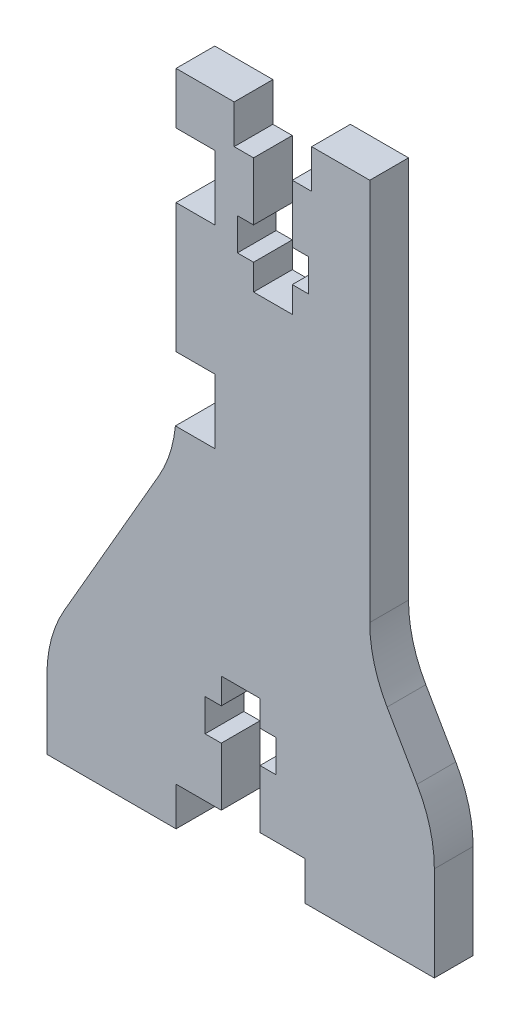
SolidWorks part; units mm, degrees
ref_plane "Alzado" through (0, 0, 0) normal (0, 0, 1) x (1, 0, 0)
ref_plane "Planta" through (0, 0, 0) normal (0, 1, 0) x (1, 0, 0)
ref_plane "Vista lateral" through (0, 0, 0) normal (1, 0, 0) x (0, 0, -1)
sketch "Croquis1" plane through (0, 0, 0) normal (0, 0, 1) x (1, 0, 0)
  line L0 (-15, -24) -> (-15, -19)
  line L1 (15, -24) -> (-15, -24)
  line L2 (15, -24) -> (15, 24) construction
  line L3 (15, 24) -> (-15, 24) construction
  line L4 (-15, -24) -> (-15, 24) construction
  line L5 (15, -24) -> (-15, 24) construction
  line L6 (15, 24) -> (-15, -24) construction
  line L7 (-15, -19) -> (-5, -1.6795)
  line L8 (-5, -1.6795) -> (-5, 24)
  line L9 (-5, 24) -> (10, 24)
  line L10 (10, 24) -> (10, -8.3397)
  line L11 (10, -8.3397) -> (15, -17)
  line L12 (15, -17) -> (15, -24)
  line L14 (-15, -24) -> (-5, -24)
  line L15 (-15, -24) -> (-15, -27)
  line L16 (-15, -27) -> (-5, -27)
  line L17 (-5, -24) -> (-5, -27)
  line L18 (15, -24) -> (5, -24)
  line L19 (15, -24) -> (15, -27)
  line L20 (15, -27) -> (5, -27)
  line L21 (5, -24) -> (5, -27)
  point P0 (0, 0)
  dimension "D1" = 48
  dimension "D2" = 30
  dimension "D3" = 10
  dimension "D4" = 5
  dimension "D5" = 5
  dimension "D6" = 7
  dimension "D7" = 3
  dimension "D8" = 10
  dimension "D9" = 10
  dimension "D10" = 30
  dimension "D11" = 30
extrude "Saliente-Extruir1" add sketch "Croquis1" along normal blind 3 contours L12 L11 L10 L9 L8 L7 L0 L1 | L17 L1 L15 L16 | L1 L21 L20 L19
fillet "Redondeo1" radius 10 4 edges at (-5, -1.6795, 1.5) (-15, -19, 1.5) (10, -8.3397, 1.5) (15, -17, 1.5)
sketch "Croquis2" plane through (0, 0, 0) normal (0, 0, 1) x (1, 0, 0)
  line L0 (-5, 24) -> (10, 24) construction
  line L1 (-0.5, 24) -> (5.5, 24)
  line L2 (-0.5, 24) -> (-0.5, 21)
  line L3 (-0.5, 21) -> (5.5, 21)
  line L4 (5.5, 24) -> (5.5, 21)
  line L5 (-5, 1) -> (-5, 24) construction
  point P6 (-0.5, 22.5)
  dimension "D1" = 3
  dimension "D2" = 6
  dimension "D3" = 4.5
extrude "Cortar-Extruir1" cut sketch "Croquis2" along normal blind 3
sketch "Croquis3" plane through (0, 0, 0) normal (0, 0, 1) x (1, 0, 0)
  line L0 (-5, 24) -> (-0.5, 24) construction
  line L1 (1, 12) -> (4, 12)
  line L2 (1, 12) -> (1, 24)
  line L3 (1, 24) -> (4, 24)
  line L4 (4, 12) -> (4, 24)
  line L5 (-0.5, 21) -> (5.5, 21) construction
  line L7 (5.25, 14) -> (-0.25, 14)
  line L8 (5.25, 14) -> (5.25, 16.5)
  line L9 (5.25, 16.5) -> (-0.25, 16.5)
  line L10 (-0.25, 14) -> (-0.25, 16.5)
  line L11 (5.25, 14) -> (-0.25, 16.5) construction
  line L12 (5.25, 16.5) -> (-0.25, 14) construction
  point P8 (2.5, 21)
  point P9 (2.5, 24)
  point P10 (2.5, 15.25)
  point P16 (2.5, 12)
  dimension "D1" = 3
  dimension "D2" = 12
  dimension "D3" = 5.5
  dimension "D4" = 2.5
  dimension "D5" = 10
extrude "Cortar-Extruir2" cut sketch "Croquis3" along normal through all contours L10 L7 L2 L9 | L4 L9 L2 L7 | L8 L9 L4 L7 | L9 L4 L3 L2 | L4 L7 L2 L1
sketch "Croquis4" plane through (0, 0, 0) normal (0, 0, 1) x (1, 0, 0)
  line L0 (-5, 1) -> (-5, 24) construction
  line L1 (-5, 20) -> (-2, 20)
  line L2 (-5, 20) -> (-5, 15)
  line L3 (-5, 15) -> (-2, 15)
  line L4 (-2, 20) -> (-2, 15)
  line L5 (-5, 24) -> (-0.5, 24) construction
  line L6 (-6, 5) -> (-2, 5)
  line L7 (-6, 5) -> (-6, 0)
  line L8 (-6, 0) -> (-2, 0)
  line L9 (-2, 5) -> (-2, 0)
  dimension "D1" = 4
  dimension "D2" = 3
  dimension "D3" = 5
  dimension "D4" = 5
  dimension "D5" = 10
  dimension "D6" = 4
  dimension "D7" = 3
extrude "Cortar-Extruir3" cut sketch "Croquis4" along normal through all
sketch "Croquis5" plane through (0, 0, 0) normal (0, 0, 1) x (1, 0, 0)
  line L8 (-5, -27) -> (5, -27) construction
  point P2 (0, -27)
  point P4 (0, -15)
  point P10 (0, -27)
  line B0 (-1.5, -27) -> (1.5, -27)
  line B1 (-1.5, -27) -> (-1.5, -15)
  line B2 (-1.5, -15) -> (1.5, -15)
  line B3 (1.5, -27) -> (1.5, -15)
  line B4 (2.75, -19.5) -> (-2.75, -19.5)
  line B5 (2.75, -19.5) -> (2.75, -17)
  line B6 (2.75, -17) -> (-2.75, -17)
  line B7 (-2.75, -19.5) -> (-2.75, -17)
  line B8 (2.75, -19.5) -> (-2.75, -17) construction
  line B9 (2.75, -17) -> (-2.75, -19.5) construction
sketch_block_instance "Bloque1-1"
sketch_block "Bloque1" parameters "D1"=3, "D2"=12, "D3"=5.5, "D4"=2.5, "D5"=10
extrude "Cortar-Extruir4" cut sketch "Croquis5" along normal through all contours B3 B4 B1 B0 | B3 B6 B1 B4 | B7 B4 B1 B6 | B5 B6 B3 B4 | B6 B3 B2 B1
